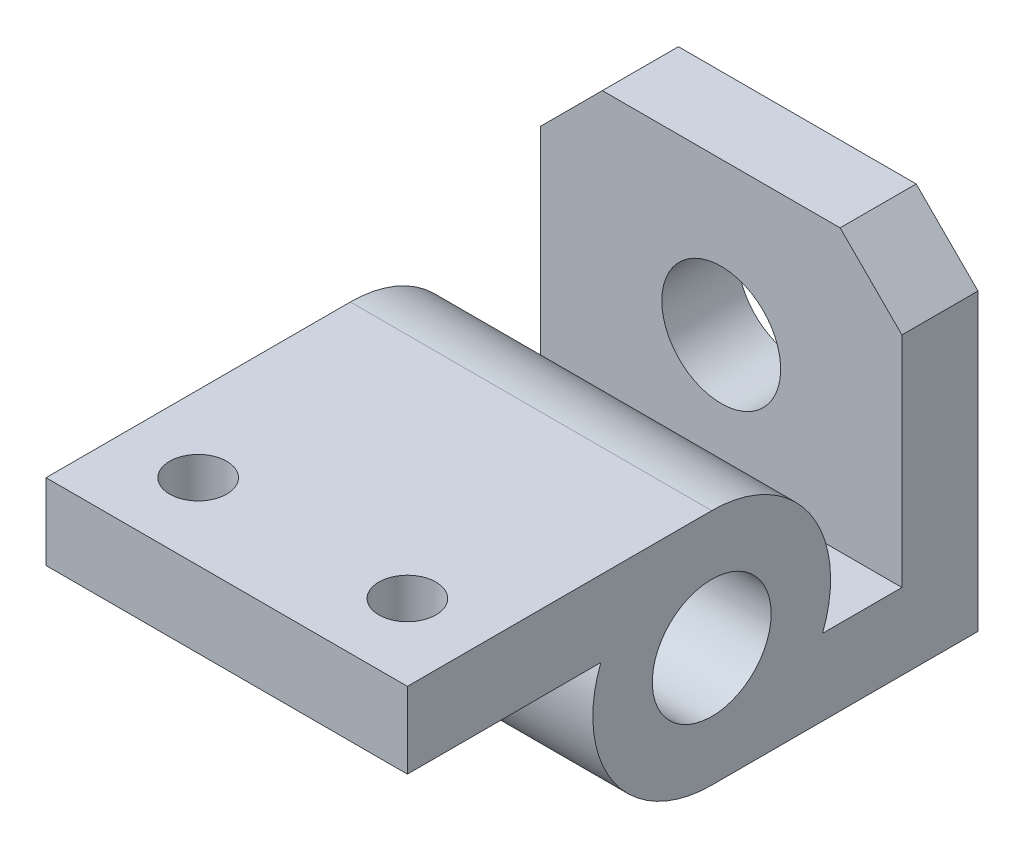
SolidWorks part; units mm, degrees
material "1345 Alloy"
ref_plane "Front Plane" through (0, 0, 0) normal (0, 0, 1) x (1, 0, 0)
ref_plane "Top Plane" through (0, 0, 0) normal (0, 1, 0) x (1, 0, 0)
ref_plane "Right Plane" through (0, 0, 0) normal (1, 0, 0) x (0, 0, -1)
sketch "Sketch1" plane through (0, 0, 0) normal (1, 0, 0) x (0, 0, -1)
  line L0 (0, 25) -> (-64, 25)
  line L1 (-64, 25) -> (-64, 9)
  line L2 (-64, 9) -> (-23.3238, 9)
  line L3 (0, -25) -> (56, -25)
  line L4 (56, -25) -> (56, 50)
  line L5 (56, 50) -> (40, 50)
  line L6 (40, 50) -> (40, -9)
  line L7 (40, -9) -> (23.3238, -9)
  arc A0 (-23.3238, 9) -> (0, -25) centre (0, 0) ccw
  circle A1 centre (0, 0) radius 12.5
  arc A2 (23.3238, -9) -> (0, 25) centre (0, 0) ccw
  dimension "D1" = 50
  dimension "D2" = 25
  dimension "D3" = 64
  dimension "D4" = 16
  dimension "D5" = 16
  dimension "D6" = 56
  dimension "D7" = 75
  dimension "D8" = 16
extrude "Boss-Extrude1" add sketch "Sketch1" along normal mid plane 76
sketch "Sketch2" plane through (0, 25, 0) normal (0, 1, 0) x (1, 0, 0)
  line L0 (38, -64) -> (-38, -64) construction
  line L1 (0, -64) -> (0, 0) construction
  circle A0 centre (-22, -48) radius 6
  circle A1 centre (22, -48) radius 6
  dimension "D1" = 12
  dimension "D2" = 44
  dimension "D3" = 16
  dimension "D4" = 22
extrude "Cut-Extrude1" cut sketch "Sketch2" against normal blind 76
sketch "Sketch3" plane through (0, 0, -56) normal (0, 0, -1) x (-1, 0, 0)
  line L0 (38, -25) -> (38, 50) construction
  line L2 (-38, 50) -> (38, 50) construction
  circle A0 centre (0, 18) radius 12.5
  point P6 (-1.7948, 50)
  dimension "D1" = 25
  dimension "D2" = 38
  dimension "D3" = 32
extrude "Cut-Extrude2" cut sketch "Sketch3" against normal up to next
chamfer "Chamfer1" distance 13 2 edges at (-38, 50, -48) (38, 50, -48)
